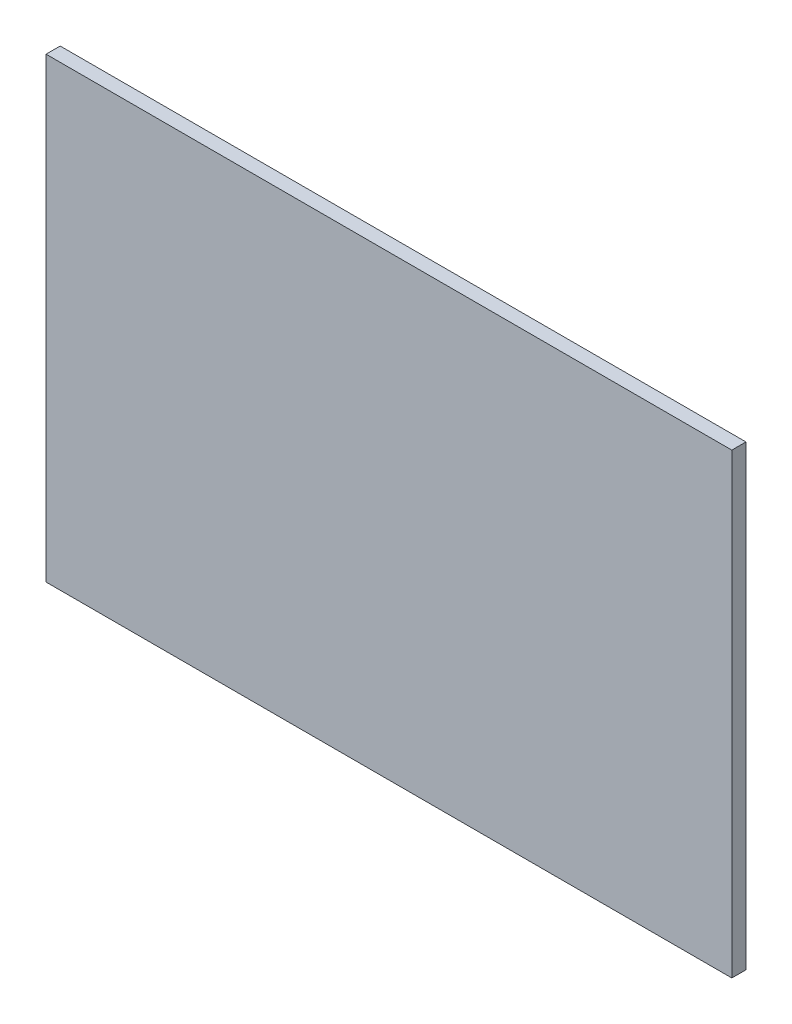
SolidWorks part; units mm, degrees
material "Maple"
ref_plane "Front Plane" through (0, 0, 0) normal (0, 0, 1) x (1, 0, 0)
ref_plane "Top Plane" through (0, 0, 0) normal (0, 1, 0) x (1, 0, 0)
ref_plane "Right Plane" through (0, 0, 0) normal (1, 0, 0) x (0, 0, -1)
sketch "Sketch1" plane through (0, 0, 0) normal (0, 0, 1) x (1, 0, 0)
  line L0 (0, 0) -> (0, -194)
  line L1 (0, 0) -> (291, 0)
  line L3 (0, -194) -> (291, -194)
  line L4 (291, 0) -> (291, -72)
  line L5 (291, -72) -> (291, -122)
  line L6 (291, -122) -> (291, -194)
  line L12 (291, -97) -> (0, -97) construction
  dimension "D1" = 291
  dimension "D2" = 72
  dimension "D4" = 72
  dimension "D6" = 194
extrude "Boss-Extrude1" add sketch "Sketch1" along normal blind 6 contours L1 L4 L5 L6 L3 L0
